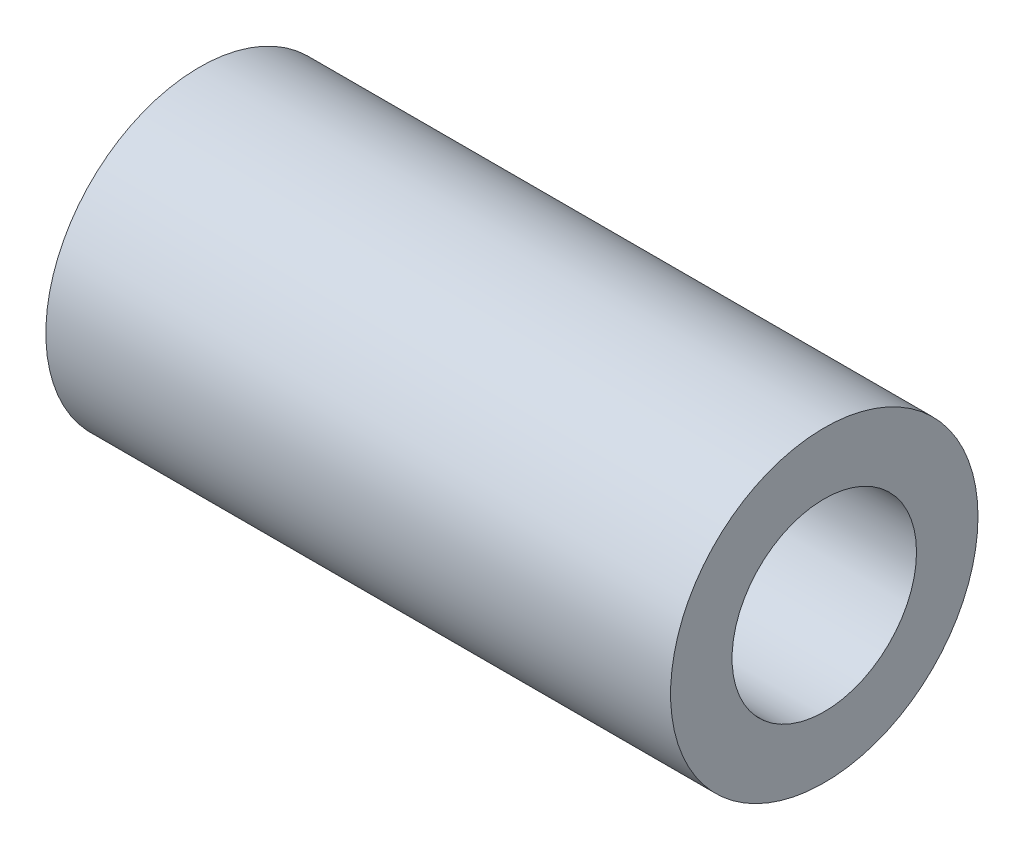
SolidWorks part; units mm, degrees
material "Thornel Mat VMA"
ref_plane "Front Plane" through (0, 0, 0) normal (0, 0, 1) x (1, 0, 0)
ref_plane "Top Plane" through (0, 0, 0) normal (0, 1, 0) x (1, 0, 0)
ref_plane "Right Plane" through (0, 0, 0) normal (1, 0, 0) x (0, 0, -1)
sketch "Sketch1" plane through (0, 0, 0) normal (1, 0, 0) x (0, 0, -1)
  circle A0 centre (0, 0) radius 4.7625
  circle A1 centre (0, 0) radius 7.9375
  dimension "D1" = 9.525
  dimension "D2" = 15.875
extrude "Boss-Extrude1" add sketch "Sketch1" along normal mid plane 32.258
